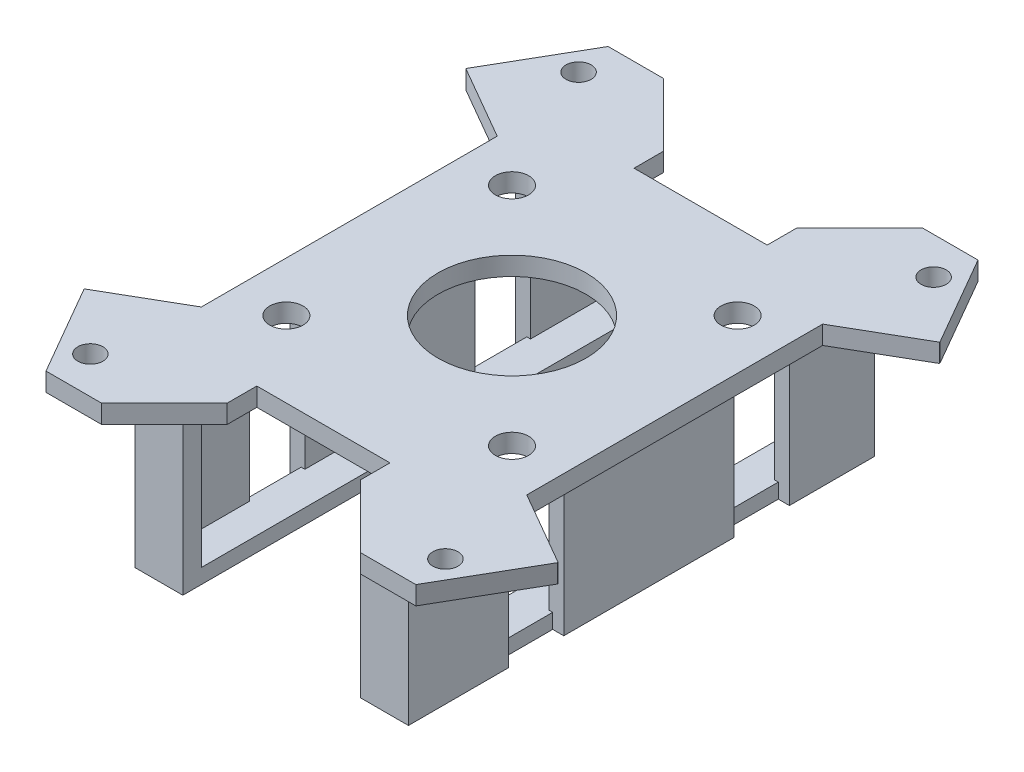
SolidWorks part; units mm, degrees
material "PET"
ref_plane "前视基准面" through (0, 0, 0) normal (0, 0, 1) x (1, 0, 0)
ref_plane "上视基准面" through (0, 0, 0) normal (0, 1, 0) x (1, 0, 0)
ref_plane "右视基准面" through (0, 0, 0) normal (1, 0, 0) x (0, 0, -1)
other "Configuration Table"
sketch "草图1" plane through (0, 0, 0) normal (0, 1, 0) x (1, 0, 0)
  line L8 (0, 0) -> (70.5208, 0) construction
  line L9 (0, 0) -> (0, 30.158) construction
  line L10 (-32, 38) -> (32, 38)
  line L11 (-32, 38) -> (-32, -38)
  line L12 (32, 38) -> (32, -38)
  line L13 (-32, -38) -> (32, -38)
  circle A1 centre (-15.25, 15.25) radius 2.25
  circle A4 centre (-24, -33) radius 1.7
  circle A12 centre (24, -33) radius 1.7
  circle A13 centre (24, 33) radius 1.7
  circle A14 centre (-24, 33) radius 1.7
  circle A15 centre (15.25, 15.25) radius 2.25
  circle A16 centre (15.25, -15.25) radius 2.25
  circle A17 centre (-15.25, -15.25) radius 2.25
  point P13 (0, 38)
  point P14 (32, 0)
  point P15 (-32, 0)
  dimension "D1" = 3.4
  dimension "D6" = 4.5
  dimension "D2" = 24
  dimension "D3" = 33
  dimension "D4" = 15.25
  dimension "D5" = 15.25
  dimension "D7" = 38
  dimension "D8" = 32
extrude "凸台-拉伸1" add sketch "草图1" along normal blind 2.5
sketch "草图2" plane through (0, 0, 0) normal (0, 1, 0) x (1, 0, 0)
  line L1 (12, -30.5) -> (17, -30.5)
  line L2 (12, -30.5) -> (12, 30.5)
  line L3 (12, 30.5) -> (17, 30.5)
  line L4 (17, -30.5) -> (17, 30.5)
  line L5 (-17, -30.5) -> (-12, -30.5)
  line L6 (-17, -30.5) -> (-17, 30.5)
  line L7 (-17, 30.5) -> (-12, 30.5)
  line L8 (-12, -30.5) -> (-12, 30.5)
extrude "凸台-拉伸2" add sketch "草图2" along normal blind 2 from offset 20
sketch "草图3" plane through (0, 0, 0) normal (0, 1, 0) x (1, 0, 0)
  line L0 (0, 0) -> (26.6049, 0) construction
  line L1 (16.5, -30.5) -> (18.5, -30.5)
  line L2 (16.5, -30.5) -> (16.5, -19)
  line L4 (18.5, -30.5) -> (18.5, -19)
  line L5 (-18.5, -30.5) -> (-16.5, -30.5)
  line L6 (-18.5, -30.5) -> (-18.5, -19)
  line L8 (-16.5, -30.5) -> (-16.5, -19)
  line L10 (16.5, -1) -> (16.5, 11.5)
  line L11 (16.5, 30.5) -> (18.5, 30.5)
  line L12 (18.5, -1) -> (18.5, 11.5)
  line L14 (-18.5, -1) -> (-18.5, 11.5)
  line L15 (-18.5, 30.5) -> (-16.5, 30.5)
  line L16 (-16.5, -1) -> (-16.5, 11.5)
  line L17 (0, 0) -> (0, 23.4889) construction
  line L18 (0, 19) -> (-41.3987, 19) construction
  line L19 (-39.8062, 11.5) -> (48.0619, 11.5) construction
  line L20 (-18.5, 19) -> (-18.5, 30.5)
  line L21 (-16.5, 19) -> (-16.5, 30.5)
  line L22 (16.5, 19) -> (16.5, 30.5)
  line L23 (18.5, 19) -> (18.5, 30.5)
  line L24 (-39.8062, -11.5) -> (48.0619, -11.5) construction
  line L25 (0, -19) -> (-41.3987, -19) construction
  line L26 (-18.5, -11.5) -> (-18.5, -1)
  line L27 (-16.5, -11.5) -> (-16.5, -1)
  line L28 (16.5, -11.5) -> (16.5, -1)
  line L29 (18.5, -11.5) -> (18.5, -1)
  line L30 (-18.5, 19) -> (-16.5, 19)
  line L31 (16.5, 19) -> (18.5, 19)
  line L32 (16.5, 11.5) -> (18.5, 11.5)
  line L33 (16.5, -11.5) -> (18.5, -11.5)
  line L34 (16.5, -19) -> (18.5, -19)
  line L35 (-18.5, -19) -> (-16.5, -19)
  line L36 (-18.5, -11.5) -> (-16.5, -11.5)
  line L37 (-18.5, 11.5) -> (-16.5, 11.5)
  dimension "D1" = 19
  dimension "D2" = 11.5
extrude "凸台-拉伸3" add sketch "草图3" along normal blind 20 from offset 20
sketch "草图4" plane through (0, 0, 0) normal (0, 1, 0) x (1, 0, 0)
  line L0 (0, 0) -> (41.8871, 0) construction
  line L1 (-18.5, -32.5) -> (-12, -32.5)
  line L2 (-18.5, -32.5) -> (-18.5, -30)
  line L3 (-18.5, -30) -> (-12, -30)
  line L4 (18.5, -32.5) -> (18.5, -30)
  line L5 (0, 0) -> (0, -8.1016) construction
  line L6 (-12, -15.1967) -> (-12, -35.3792) construction
  line L7 (12, -15.1967) -> (12, -35.3792) construction
  line L8 (12, -30) -> (18.5, -30)
  line L9 (12, -32.5) -> (18.5, -32.5)
  line L12 (-12, -32.5) -> (-12, -30)
  line L13 (12, -30) -> (12, -32.5)
  dimension "D1" = 12
extrude "凸台-拉伸4" add sketch "草图4" along normal blind 20 from offset 20
sketch "草图5" plane through (0, 0, 0) normal (0, -1, 0) x (1, 0, 0)
  line L0 (0, 0) -> (60.2444, 0) construction
  line L1 (0, 0) -> (0, 22.0297) construction
  line L2 (-22, 20) -> (-22, -20)
  line L3 (-22, 20) -> (-32, 25.7735)
  line L4 (-32, -38) -> (-32, 38) construction
  line L5 (-22, -20) -> (-32, -25.7735)
  line L6 (-32, 25.7735) -> (-32, -25.7735)
  line L7 (22, 20) -> (32, 25.7735)
  line L8 (22, 20) -> (22, -20)
  line L9 (22, -20) -> (32, -25.7735)
  line L10 (32, 25.7735) -> (32, -25.7735)
  line L11 (-17.5, 38) -> (17.5, 38)
  line L12 (-32, 38) -> (32, 38) construction
  line L13 (-17.5, 38) -> (-9, 29.5)
  line L14 (-9, 29.5) -> (9, 29.5) construction
  line L15 (17.5, 38) -> (9, 29.5)
  line L20 (-32, -25.8756) -> (-25, -38)
  line L21 (32, -38) -> (-32, -38) construction
  line L22 (-32, -25.8756) -> (-32, -38)
  line L23 (-32, -38) -> (-25, -38)
  line L24 (32, -25.8756) -> (32, -38)
  line L25 (32, -25.8756) -> (25, -38)
  line L26 (32, -38) -> (25, -38)
  line L27 (32, 25.8756) -> (25, 38)
  line L28 (32, 38) -> (25, 38)
  line L29 (32, 25.8756) -> (32, 38)
  line L30 (-32, 25.8756) -> (-32, 38)
  line L31 (-32, 25.8756) -> (-25, 38)
  line L32 (-32, 38) -> (-25, 38)
  line L33 (-9, 29.5) -> (-9, 25.5)
  line L34 (-9, 25.5) -> (9, 25.5)
  line L35 (9, 29.5) -> (9, 25.5)
  line L36 (17.5, -38) -> (9, -29.5)
  line L37 (-17.5, -38) -> (17.5, -38)
  line L38 (-17.5, -38) -> (-9, -29.5)
  line L39 (-9, -29.5) -> (-9, -25.5)
  line L40 (-9, -25.5) -> (9, -25.5)
  line L41 (9, -29.5) -> (9, -25.5)
  circle A0 centre (0, 0) radius 10
  point P7 (-22, 0)
  point P22 (0, 29.5)
  point P23 (0, 38)
  point P45 (0, 25.5)
  dimension "D10" = 20
  dimension "D1" = 22
  dimension "D2" = 40
  dimension "D3" = 30
  dimension "D4" = 17.5
  dimension "D5" = 135
  dimension "D6" = 9
  dimension "D7" = 120
  dimension "D8" = 7
  dimension "D9" = 4
extrude "切除-拉伸1" cut sketch "草图5" against normal blind 10
